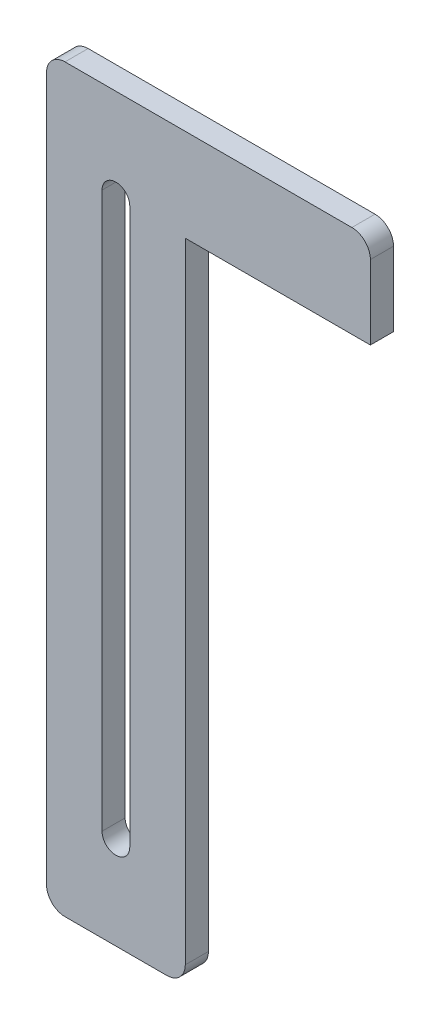
SolidWorks part; units mm, degrees
ref_plane "Front Plane" through (0, 0, 0) normal (0, 0, 1) x (1, 0, 0)
ref_plane "Top Plane" through (0, 0, 0) normal (0, 1, 0) x (1, 0, 0)
ref_plane "Right Plane" through (0, 0, 0) normal (1, 0, 0) x (0, 0, -1)
sketch "Sketch1" plane through (0, 0, 0) normal (0, 0, 1) x (1, 0, 0)
  line L0 (9.525, 101.6) -> (9.525, 0) construction
  line L1 (0, 0) -> (19.05, 0)
  line L2 (0, 0) -> (0, 101.6)
  line L3 (0, 101.6) -> (19.05, 101.6)
  line L4 (19.05, 0) -> (19.05, 101.6)
  line L5 (19.05, 101.6) -> (44.45, 101.6)
  line L6 (19.05, 101.6) -> (19.05, 88.9)
  line L7 (19.05, 88.9) -> (44.45, 88.9)
  line L8 (44.45, 101.6) -> (44.45, 88.9)
  line L9 (9.525, 88.9) -> (9.525, 12.7) construction
  line L10 (11.43, 88.9) -> (11.43, 12.7)
  line L11 (7.62, 88.9) -> (7.62, 12.7)
  arc A0 (11.43, 88.9) -> (7.62, 88.9) centre (9.525, 88.9) ccw
  arc A1 (7.62, 12.7) -> (11.43, 12.7) centre (9.525, 12.7) ccw
  point P12 (9.525, 50.8)
  dimension "D1" = 19.05
  dimension "D2" = 101.6
  dimension "D3" = 25.4
  dimension "D4" = 12.7
  dimension "D5" = 3.81
  dimension "D6" = 12.7
  dimension "D7" = 76.2
extrude "Boss-Extrude1" add sketch "Sketch1" along normal blind 3.175 contours L8 L5 L4 L7 | L11 A1 L10 A0
fillet "Fillet1" radius 2.54 4 edges at (19.05, 0, 1.5875) (0, 0, 1.5875) (44.45, 101.6, 1.5875) (0, 101.6, 1.5875)
